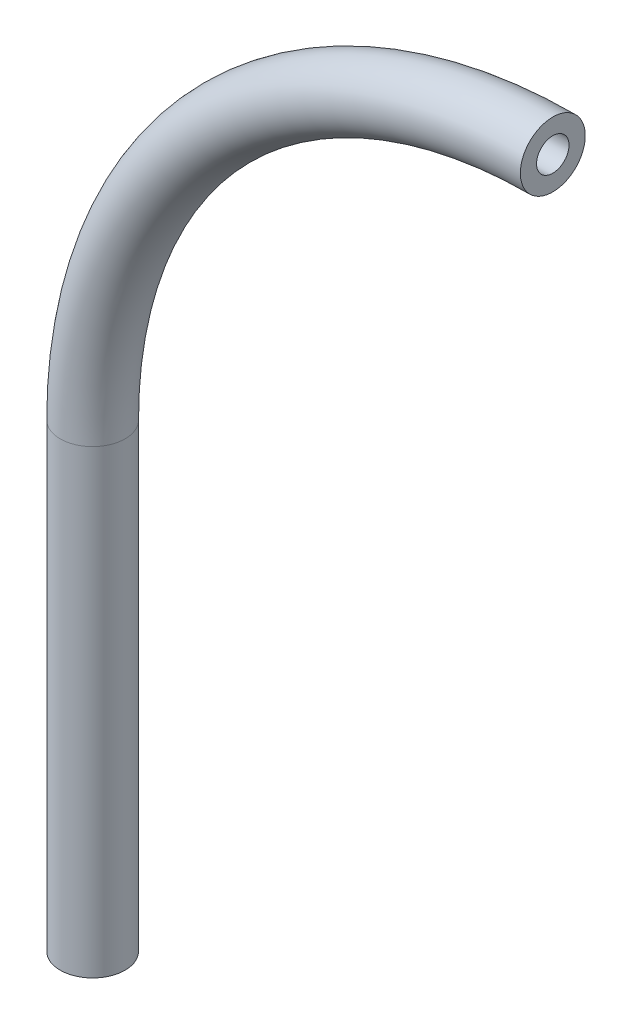
SolidWorks part; units mm, degrees
ref_plane "Front Plane" through (0, 0, 0) normal (0, 0, 1) x (1, 0, 0)
ref_plane "Top Plane" through (0, 0, 0) normal (0, 1, 0) x (1, 0, 0)
ref_plane "Right Plane" through (0, 0, 0) normal (1, 0, 0) x (0, 0, -1)
sketch "Sketch1" plane through (0, 0, 0) normal (0, 1, 0) x (1, 0, 0)
  circle A0 centre (0, 0) radius 3.175
  circle A1 centre (0, 0) radius 1.5875
  dimension "D1" = 3.175
  dimension "D2" = 6.35
sketch "Sketch2" plane through (0, 0, 0) normal (0, 0, 1) x (1, 0, 0)
  line L0 (0, 0) -> (45, 0) construction
  line L1 (45, 0) -> (45, 45) construction
  line L2 (0, 0) -> (0, -15)
  arc A0 (0, 0) -> (45, 45) centre (45, 0) cw
  dimension "D3" = 45
  dimension "D1" = 45
  dimension "D2" = 45
  dimension "D4" = 15
sweep "Sweep1" add profiles "Sketch1" path "Sketch2"
sketch "Sketch3" plane through (0, 0, 0) normal (0, -1, 0) x (1, 0, 0)
  circle A0 centre (0, 0) radius 1.5875
  circle A1 centre (0, 0) radius 3.175
extrude "Boss-Extrude1" add sketch "Sketch3" along normal blind 45
